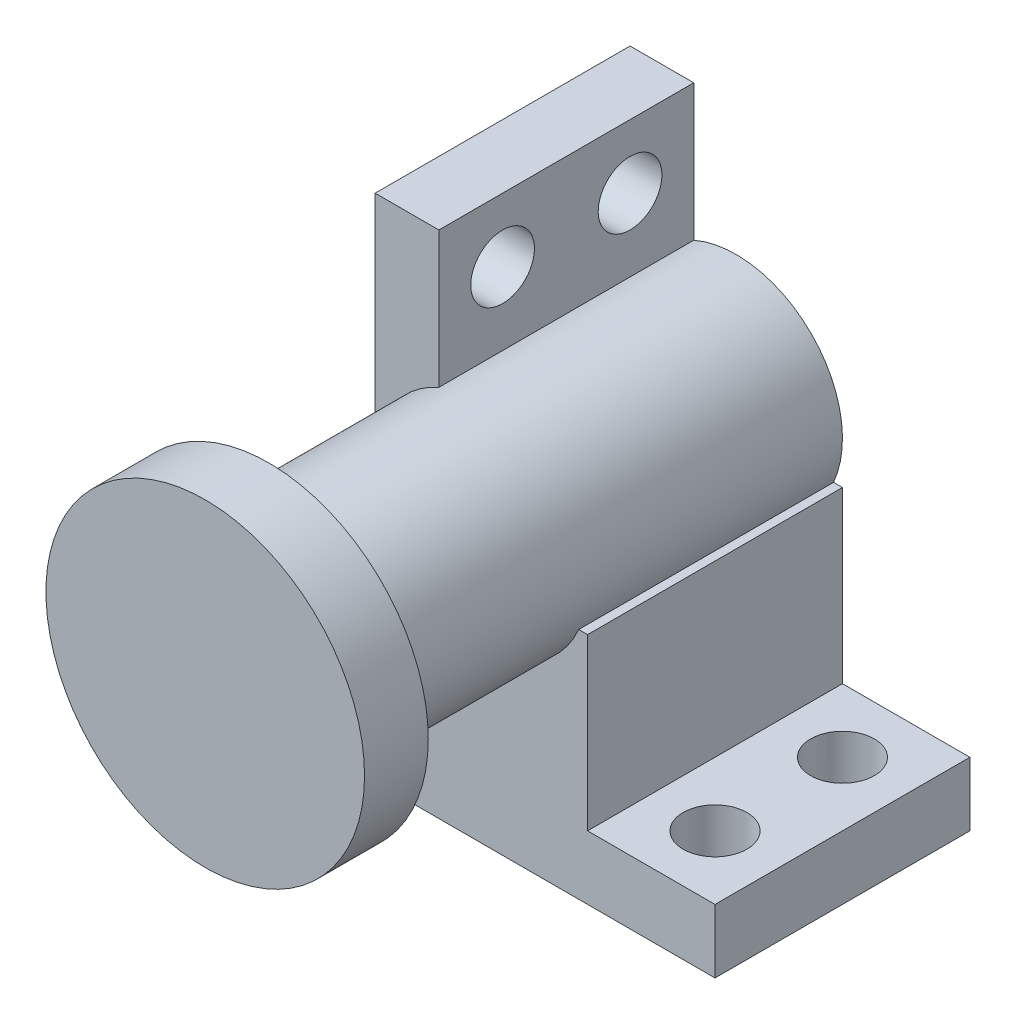
SolidWorks part; units mm, degrees
ref_plane "前视基准面" through (0, 0, 0) normal (0, 0, 1) x (1, 0, 0)
ref_plane "上视基准面" through (0, 0, 0) normal (0, 1, 0) x (1, 0, 0)
ref_plane "右视基准面" through (0, 0, 0) normal (1, 0, 0) x (0, 0, -1)
sketch "草图1" plane through (0, 0, 0) normal (0, 0, 1) x (1, 0, 0)
  line L0 (-5, 0) -> (-5, 11)
  line L1 (-5, 11) -> (-2, 11)
  line L2 (-2, 11) -> (-2, 4.5826)
  line L3 (0, -5) -> (11, -5)
  line L4 (-5, 0) -> (-5, -5)
  line L5 (-5, -5) -> (0, -5)
  line L6 (11, -5) -> (11, -2)
  line L7 (11, -2) -> (4.5826, -2)
  line L8 (11, -5) -> (11, -13)
  line L9 (11, -13) -> (-5, -13)
  line L10 (-5, -13) -> (-5, -5)
  line L11 (0, 0) -> (0, -13) construction
  arc A0 (4.5826, -2) -> (-2, 4.5826) centre (0, 0) ccw
  point P13 (0, 0)
extrude "凸台-拉伸1" add sketch "草图1" along normal blind 12 contours L7 A0 L2 L1 L0 L4 L5 L3 L6 | L10 L9 L8 L3 L5 | L11 L5 L10 L9
sketch "草图2" plane through (0, 0, 12) normal (0, 0, 1) x (1, 0, 0)
  circle A0 centre (0, 0) radius 5
extrude "凸台-拉伸2" add sketch "草图2" along normal blind 10
sketch "草图3" plane through (0, 0, 22) normal (0, 0, 1) x (1, 0, 0)
  circle A0 centre (0, 0) radius 7.5
extrude "凸台-拉伸3" add sketch "草图3" along normal blind 3
sketch "草图4" plane through (-2, 0, 0) normal (1, 0, 0) x (0, 0, -1)
  line L0 (-12, 11) -> (-12, 4.9971)
  line L2 (-12, 7.9985) -> (-9, 7.9985)
  line L3 (0, 7.9985) -> (-3, 7.9985)
  circle A0 centre (-9, 7.9985) radius 1.5
  circle A1 centre (-3, 7.9985) radius 1.5
extrude "切除-拉伸1" cut sketch "草图4" against normal blind 3
sketch "草图5" plane through (0, -2, 0) normal (0, 1, 0) x (1, 0, 0)
  line L0 (11, -12) -> (5, -12)
  line L1 (5, -22) -> (5, 0) construction
  line L3 (8, -12) -> (8, -9)
  line L4 (8, 0) -> (8, -3)
  circle A0 centre (8, -9) radius 1.5
  circle A1 centre (8, -3) radius 1.5
extrude "切除-拉伸2" cut sketch "草图5" against normal blind 11
sketch "草图6" plane through (0, -2, 0) normal (0, 1, 0) x (1, 0, 0)
  line L1 (5, 0) -> (11, 0)
  line L2 (5, 0) -> (5, -12)
  line L3 (5, -12) -> (11, -12)
  line L4 (11, 0) -> (11, -12)
extrude "切除-拉伸3" cut sketch "草图6" against normal blind 8
